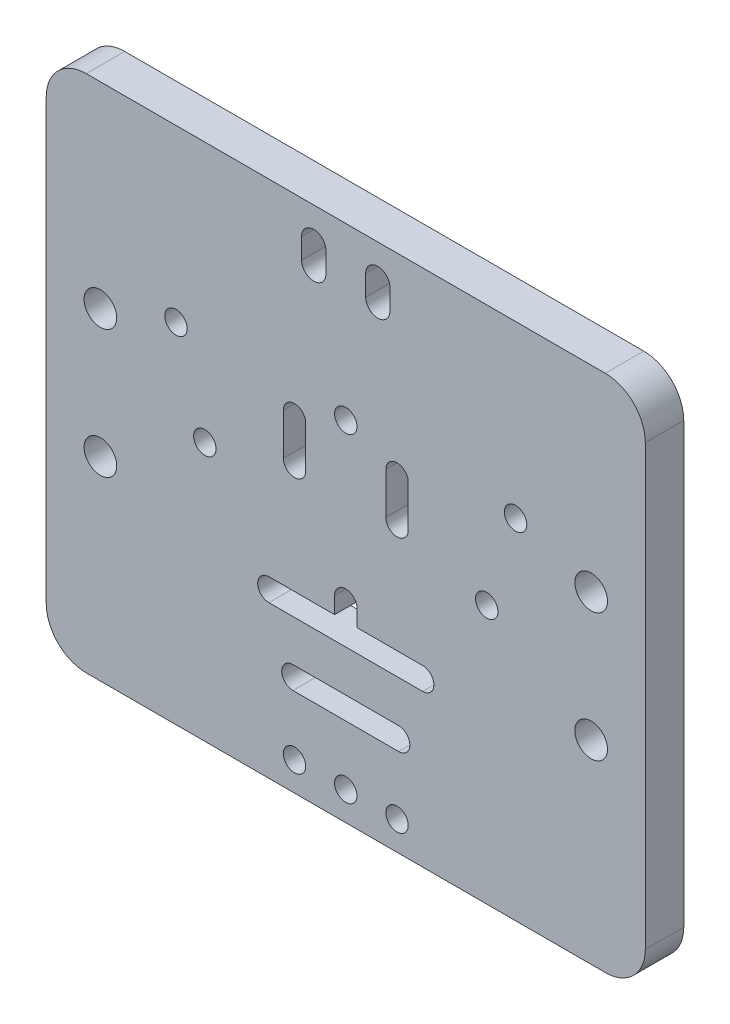
SolidWorks part; units mm, degrees
material "Acrylic (Medium-high impact)"
ref_plane "Спереди" through (0, 0, 0) normal (0, 0, 1) x (1, 0, 0)
ref_plane "Сверху" through (0, 0, 0) normal (0, 1, 0) x (1, 0, 0)
ref_plane "Справа" through (0, 0, 0) normal (1, 0, 0) x (0, 0, -1)
sketch "Model" plane through (0, 0, 0) normal (0, 0, 1) x (1, 0, 0)
  line L0 (0, 0) -> (0, 91.7343) construction
  line L1 (5, 79.6063) -> (5, 68.5159) construction
  line L2 (-2.3648, 54.4) -> (2.3481, 54.4) construction
  line L3 (8, 54.1038) -> (8, 41.41) construction
  line L4 (38.3, 55.3072) -> (38.3, 25.5369) construction
  line L6 (5.2056, 25.5) -> (38.932, 25.5) construction
  line L9 (8, 7.117) -> (8, 1.8707) construction
  line L13 (34.6862, 30.35) -> (41.936, 30.35) construction
  line L14 (34.5552, 50.35) -> (42.4898, 50.35) construction
  line L15 (26.5, 56.989) -> (26.5, 51.9054) construction
  line L16 (23.9154, 54.4) -> (29.241, 54.4) construction
  line L17 (22, 42.5983) -> (22, 38.5529) construction
  line L18 (19.8952, 40.4) -> (24.0146, 40.4) construction
  line L19 (-5, 79.6063) -> (-5, 68.5159) construction
  line L20 (-3.1, 75.8) -> (-3.1, 72.6)
  line L21 (-6.9, 72.6) -> (-6.9, 75.8)
  line L22 (-6.9, 75.8) -> (-6.9, 72.6)
  line L23 (-3.1, 72.6) -> (-3.1, 75.8)
  line L24 (-34.5552, 50.35) -> (-42.4898, 50.35) construction
  line L25 (-34.6862, 30.35) -> (-41.936, 30.35) construction
  line L26 (-38.3, 55.3072) -> (-38.3, 25.5369) construction
  line L27 (-8, 7.117) -> (-8, 1.8707) construction
  line L33 (-19.8952, 40.4) -> (-24.0146, 40.4) construction
  line L34 (-22, 42.5983) -> (-22, 38.5529) construction
  line L35 (-23.9154, 54.4) -> (-29.241, 54.4) construction
  line L36 (-26.5, 56.989) -> (-26.5, 51.9054) construction
  line L37 (-8, 54.1038) -> (-8, 41.41) construction
  line L38 (-9.75, 50.9) -> (-9.75, 44.4)
  line L39 (-6.25, 44.4) -> (-6.25, 50.9)
  line L40 (-6.25, 50.9) -> (-6.25, 44.4)
  line L41 (-9.75, 44.4) -> (-9.75, 50.9)
  line L42 (-8.25, 15.5) -> (8.25, 15.5) construction
  line L1661 (3.1, 72.6) -> (3.1, 75.8)
  line L1674 (6.9, 75.8) -> (6.9, 72.6)
  line L1730 (46.75, 74.75) -> (46.75, 6.25)
  line L1743 (40.5, 0) -> (-40.5, 0)
  line L1756 (-46.75, 6.25) -> (-46.75, 74.75)
  line L1769 (-40.5, 81) -> (40.5, 81)
  line L1807 (8.25, 17.25) -> (-8.25, 17.25)
  line L1820 (-8.25, 13.75) -> (8.25, 13.75)
  line L2052 (6.9, 72.6) -> (6.9, 75.8)
  line L2065 (3.1, 75.8) -> (3.1, 72.6)
  line L2109 (9.75, 44.4) -> (9.75, 50.9)
  line L2122 (6.25, 50.9) -> (6.25, 44.4)
  line L2254 (-1.75, 29.85) -> (-1.75, 27.25)
  line L2255 (-1.75, 27.25) -> (-12, 27.25)
  line L2268 (-12, 23.75) -> (12, 23.75)
  line L2281 (12, 27.25) -> (1.75, 27.25)
  line L2282 (1.75, 27.25) -> (1.75, 29.85)
  line L2413 (6.25, 44.4) -> (6.25, 50.9)
  line L2426 (9.75, 50.9) -> (9.75, 44.4)
  line L2519 (8.25, 13.75) -> (-8.25, 13.75)
  line L2532 (-8.25, 17.25) -> (8.25, 17.25)
  line L2808 (1.75, 29.85) -> (1.75, 27.25)
  line L2809 (1.75, 27.25) -> (12, 27.25)
  line L2822 (12, 23.75) -> (-12, 23.75)
  line L2835 (-12, 27.25) -> (-1.75, 27.25)
  line L2836 (-1.75, 27.25) -> (-1.75, 29.85)
  arc A0 (-46.75, 74.75) -> (-40.5, 81) centre (-40.5, 74.75) cw
  arc A1 (40.5, 81) -> (46.75, 74.75) centre (40.5, 74.75) cw
  arc A2 (46.75, 6.25) -> (40.5, 0) centre (40.5, 6.25) cw
  arc A3 (-46.75, 6.25) -> (-40.5, 0) centre (-40.5, 6.25) ccw
  arc A4 (6.9, 75.8) -> (3.1, 75.8) centre (5, 75.8) ccw
  arc A5 (3.1, 72.6) -> (6.9, 72.6) centre (5, 72.6) ccw
  circle A7 centre (0, 4.5) radius 1.75
  circle A8 centre (8, 4.5) radius 1.75
  arc A11 (-8.25, 17.25) -> (-8.25, 13.75) centre (-8.25, 15.5) ccw
  arc A12 (8.25, 13.75) -> (8.25, 17.25) centre (8.25, 15.5) ccw
  arc A13 (1.75, 29.85) -> (-1.75, 29.85) centre (0, 29.85) ccw
  arc A14 (12, 23.75) -> (12, 27.25) centre (12, 25.5) ccw
  arc A15 (-12, 23.75) -> (-12, 27.25) centre (-12, 25.5) cw
  circle A16 centre (38.3, 50.35) radius 2.55
  circle A17 centre (38.3, 30.35) radius 2.55
  arc A18 (-3.1, 72.6) -> (-6.9, 72.6) centre (-5, 72.6) cw
  arc A19 (-6.9, 75.8) -> (-3.1, 75.8) centre (-5, 75.8) cw
  circle A20 centre (-38.3, 30.35) radius 2.55
  circle A21 centre (-38.3, 50.35) radius 2.55
  circle A22 centre (-8, 4.5) radius 1.75
  circle A26 centre (0, 54.4) radius 1.75
  circle A27 centre (26.5, 54.4) radius 1.75
  circle A28 centre (22, 40.4) radius 1.75
  arc A29 (9.75, 50.9) -> (6.25, 50.9) centre (8, 50.9) ccw
  arc A30 (9.75, 44.4) -> (6.25, 44.4) centre (8, 44.4) cw
  circle A31 centre (-22, 40.4) radius 1.75
  circle A32 centre (-26.5, 54.4) radius 1.75
  arc A33 (-9.75, 44.4) -> (-6.25, 44.4) centre (-8, 44.4) ccw
  arc A34 (-9.75, 50.9) -> (-6.25, 50.9) centre (-8, 50.9) cw
  dimension "D1" = 6.25
  dimension "D7" = 1.9
  dimension "D9" = 15.5
  dimension "D15" = 3.5
  dimension "D17" = 3.5
  dimension "D41" = 5.1
  dimension "D43" = 3.5
  dimension "D44" = 3.5
  dimension "D2" = 81
  dimension "D3" = 81
  dimension "D4" = 5
  dimension "D5" = 3.2
  dimension "D6" = 3.8
  dimension "D8" = 5.2
  dimension "D10" = 16
  dimension "D11" = 25.5
  dimension "D12" = 4.5
  dimension "D13" = 8
  dimension "D22" = 3.5
  dimension "D23" = 2.6
  dimension "D24" = 3.5
  dimension "D25" = 3.5
  dimension "D26" = 16.5
  dimension "D29" = 24
  dimension "D33" = 8
  dimension "D34" = 22
  dimension "D35" = 26.5
  dimension "D36" = 38.3
  dimension "D37" = 20
  dimension "D38" = 30.35
  dimension "D39" = 26.6
  dimension "D40" = 40.6
  dimension "D46" = 6.5
  dimension "D48" = 3.5
extrude "Base" add sketch "Model" along normal blind 6
